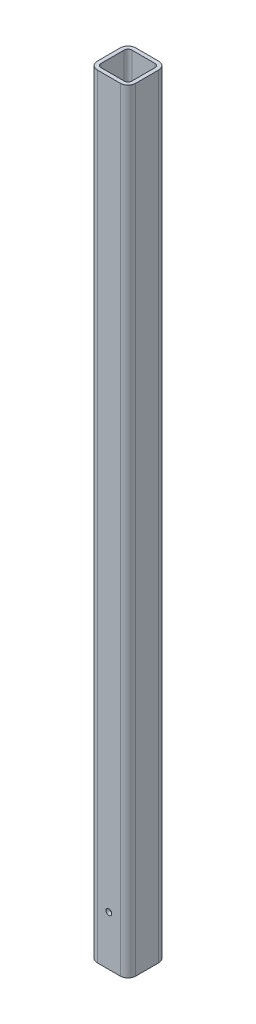
SolidWorks part; units mm, degrees
ref_plane "Plano frontal" through (0, 0, 0) normal (0, 0, 1) x (1, 0, 0)
ref_plane "Plano superior" through (0, 0, 0) normal (0, 1, 0) x (1, 0, 0)
ref_plane "Plano direito" through (0, 0, 0) normal (1, 0, 0) x (0, 0, -1)
sketch "Esboço1" plane through (0, 0, 0) normal (0, 0, 1) x (1, 0, 0)
  line L0 (0, 1060.7614) -> (0, 1866.9998)
  line L1 (0, 0) -> (0, 1500) construction
other "Componente estrutural1"
ref_plane "Plano4" through (0, 1060.7614, 0) normal (0, 1, 0) x (-1, 0, 0)
sketch "Sketch1" plane through (0, 1060.7614, 0) normal (0, 1, 0) x (-1, 0, 0)
  line L0 (-12, -16) -> (12, -16)
  line L1 (-16, -12) -> (-16, 12)
  line L2 (12, 16) -> (-12, 16)
  line L3 (16, 12) -> (16, -12)
  line L4 (-12, -20) -> (12, -20)
  line L5 (-20, -12) -> (-20, 12)
  line L6 (12, 20) -> (-12, 20)
  line L7 (20, 12) -> (20, -12)
  arc A0 (20, 12) -> (12, 20) centre (12, 12) ccw
  arc A1 (12, -20) -> (20, -12) centre (12, -12) ccw
  arc A2 (-20, -12) -> (-12, -20) centre (-12, -12) ccw
  arc A3 (-12, 20) -> (-20, 12) centre (-12, 12) ccw
  arc A4 (-12, 16) -> (-16, 12) centre (-12, 12) ccw
  arc A5 (16, 12) -> (12, 16) centre (12, 12) ccw
  arc A6 (12, -16) -> (16, -12) centre (12, -12) ccw
  arc A7 (-16, -12) -> (-12, -16) centre (-12, -12) ccw
  point P0 (-20, 0)
  point P1 (20, 0)
  point P2 (0, 20)
  point P3 (0, -20)
  point P4 (0, 0)
  point P5 (-20, -20)
  point P6 (20, -20)
  point P7 (20, 20)
  point P8 (-20, 20)
  point P33 (0, 0)
  dimension "D1" = 8
  dimension "Thickness" = 4
  dimension "V_leg" = 40
sketch "Esboço3" plane through (0, 0, -20) normal (0, 0, -1) x (-1, 0, 0)
  line L0 (0, 1060.7614) -> (0, 1866.9998) construction
  circle A0 centre (0, 1112.6041) radius 3
extrude "Corte-extrusão1" cut sketch "Esboço3" against normal blind 76 contours A0
